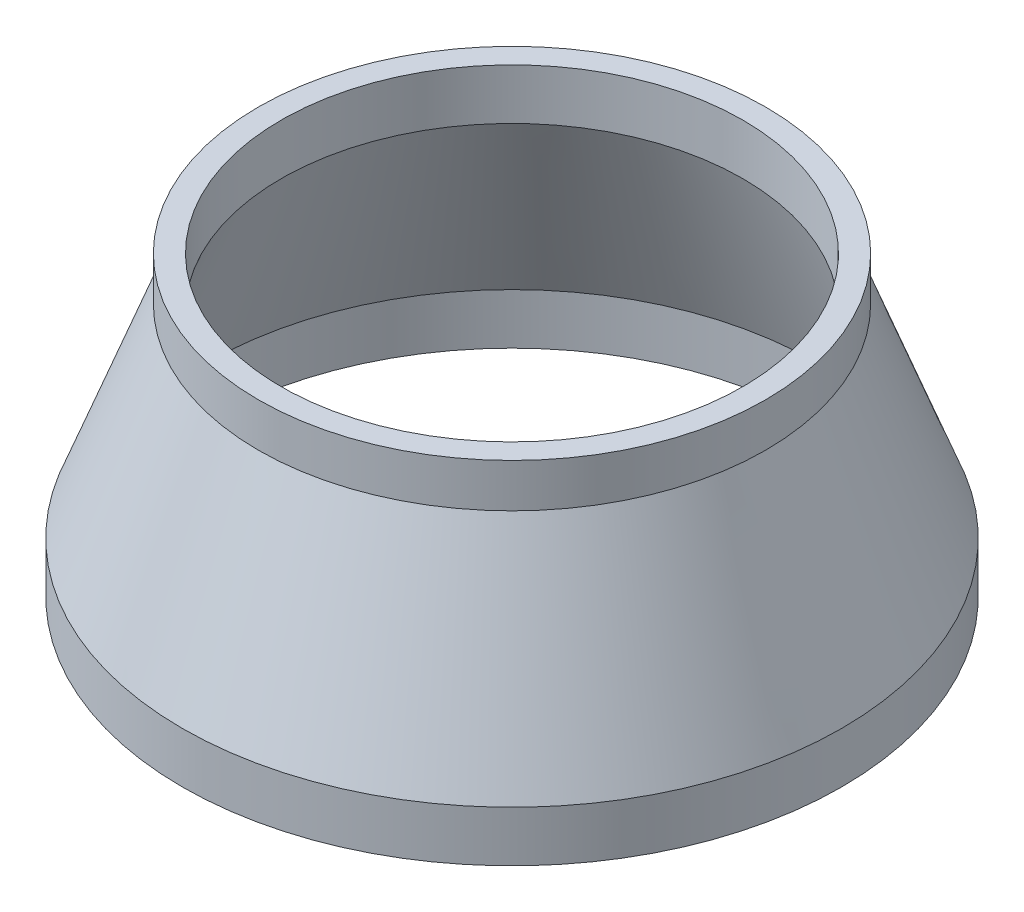
SolidWorks part; units mm, degrees
ref_plane "Front Plane" through (0, 0, 0) normal (0, 0, 1) x (1, 0, 0)
ref_plane "Top Plane" through (0, 0, 0) normal (0, 1, 0) x (1, 0, 0)
ref_plane "Right Plane" through (0, 0, 0) normal (1, 0, 0) x (0, 0, -1)
sketch "Sketch1" plane through (0, 0, 0) normal (0, 0, 1) x (1, 0, 0)
  line L0 (0, 0) -> (38.1, 0) construction
  line L1 (0, 0) -> (0, 25.4) construction
  line L2 (38.1, 0) -> (28.907, 24.5147)
  line L3 (28.907, 24.5147) -> (28.907, 30.8647)
  line L4 (28.907, 30.8647) -> (31.75, 30.8647)
  line L5 (31.75, 30.8647) -> (31.75, 25.4)
  line L6 (31.75, 25.4) -> (41.275, 0)
  line L7 (41.275, 0) -> (41.275, -6.35)
  line L8 (41.275, -6.35) -> (38.1, -6.35)
  line L9 (38.1, -6.35) -> (38.1, 0)
  dimension "D1" = 25.4
  dimension "D2" = 41.275
  dimension "D3" = 31.75
  dimension "D4" = 6.35
revolve "Revolve3" add sketch "Sketch1" angle 360 about L1
